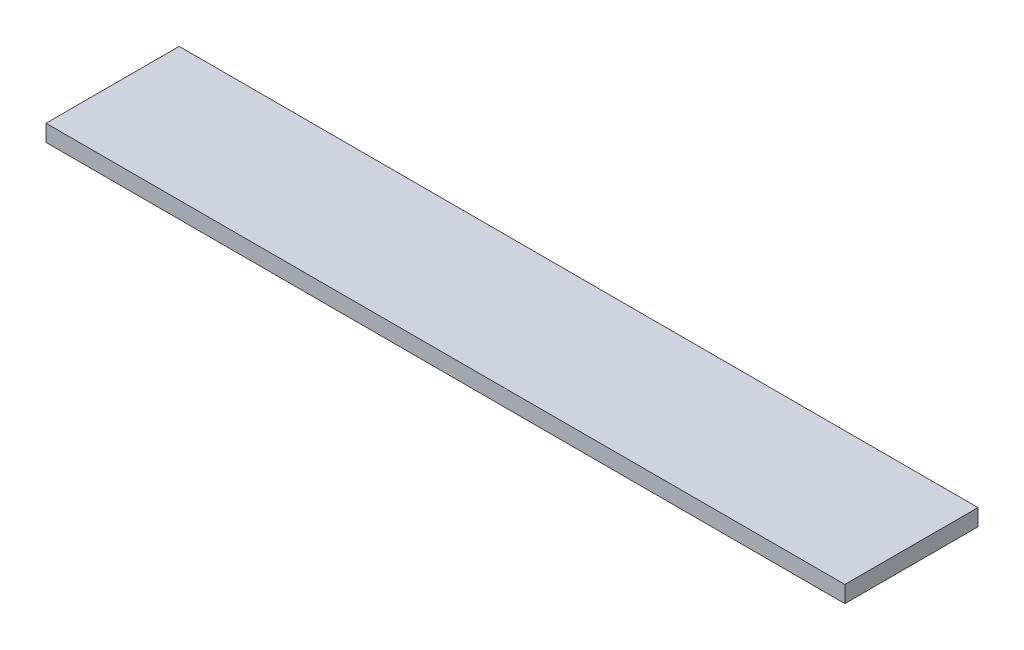
SolidWorks part; units mm, degrees
material "ABS"
ref_plane "Front" through (0, 0, 0) normal (0, 0, 1) x (1, 0, 0)
ref_plane "Top" through (0, 0, 0) normal (0, 1, 0) x (1, 0, 0)
ref_plane "Right" through (0, 0, 0) normal (1, 0, 0) x (0, 0, -1)
sketch "Sketch1" plane through (0, 0, 0) normal (0, 1, 0) x (1, 0, 0)
  line L1 (-38.1, -6.35) -> (38.1, -6.35)
  line L2 (-38.1, -6.35) -> (-38.1, 6.35)
  line L3 (-38.1, 6.35) -> (38.1, 6.35)
  line L4 (38.1, -6.35) -> (38.1, 6.35)
  line L5 (-38.1, -6.35) -> (38.1, 6.35) construction
  line L6 (-38.1, 6.35) -> (38.1, -6.35) construction
  point P0 (0, 0)
  dimension "D1" = 76.2
  dimension "D2" = 12.7
extrude "Boss-Extrude1" add sketch "Sketch1" along normal blind 1.5875
